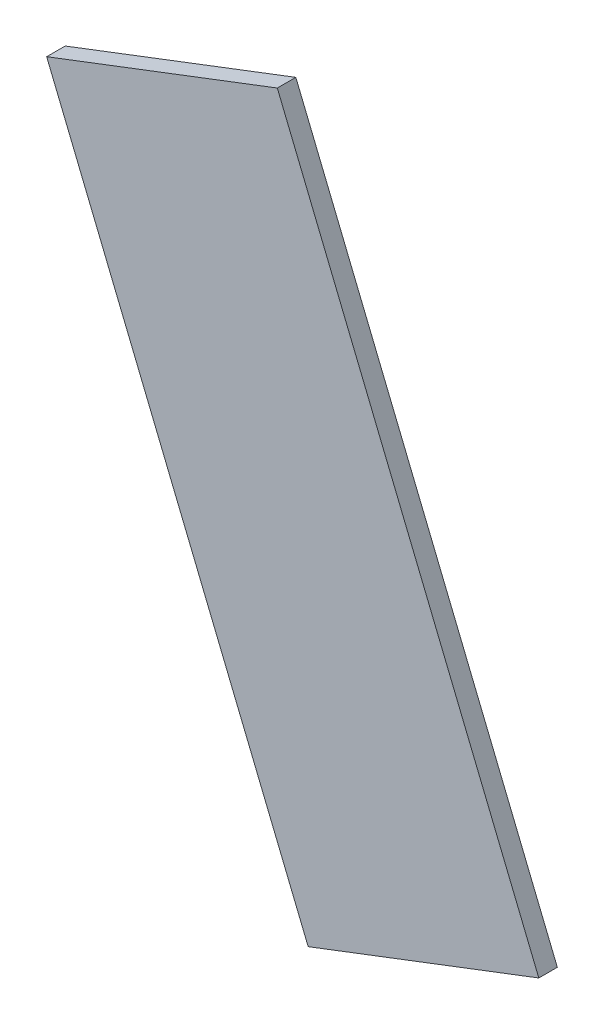
SolidWorks part; units mm, degrees
ref_plane "Front Plane" through (0, 0, 0) normal (0, 0, 1) x (1, 0, 0)
ref_plane "Top Plane" through (0, 0, 0) normal (0, 1, 0) x (1, 0, 0)
ref_plane "Right Plane" through (0, 0, 0) normal (1, 0, 0) x (0, 0, -1)
sketch "Sketch1" plane through (0, 0, 0) normal (0, 0, 1) x (1, 0, 0)
  line L0 (-21.7566, 68.9267) -> (20.6069, -34.7523)
  line L1 (20.6069, -34.7523) -> (-16.7552, -49.0378)
  line L2 (-16.7552, -49.0378) -> (-59.1187, 54.6412)
  line L3 (-59.1187, 54.6412) -> (-21.7566, 68.9267)
  point P4 (18.5289, -38.9176)
  point P5 (-13.0862, -51.0057)
  dimension "D1" = 40
  dimension "D2" = 112
extrude "Boss-Extrude1" add sketch "Sketch1" along normal blind 3
